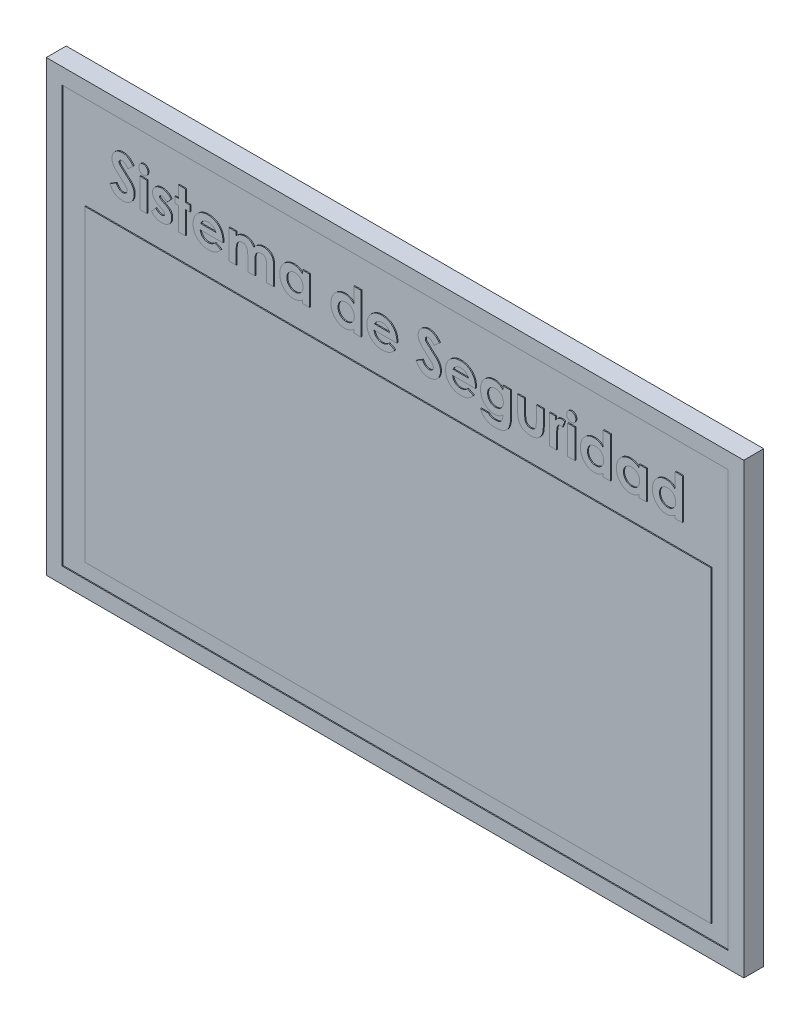
SolidWorks part; units mm, degrees
ref_plane "Alzado" through (0, 0, 0) normal (0, 0, 1) x (1, 0, 0)
ref_plane "Planta" through (0, 0, 0) normal (0, 1, 0) x (1, 0, 0)
ref_plane "Vista lateral" through (0, 0, 0) normal (1, 0, 0) x (0, 0, -1)
sketch "Croquis1" plane through (0, 0, 0) normal (0, 0, 1) x (1, 0, 0)
  line L1 (-350, -225) -> (350, -225)
  line L2 (-350, -225) -> (-350, 225)
  line L3 (-350, 225) -> (350, 225)
  line L4 (350, -225) -> (350, 225)
  line L5 (-350, -225) -> (350, 225) construction
  line L6 (-350, 225) -> (350, -225) construction
  point P0 (0, 0)
  dimension "D1" = 450
  dimension "D2" = 700
extrude "Saliente-Extruir1" add sketch "Croquis1" along normal blind 20
sketch "Croquis2" plane through (0, 0, 20) normal (0, 0, 1) x (1, 0, 0)
  line L0 (350, 225) -> (-350, 225) construction
  line L1 (334, -209) -> (-334, -209)
  line L2 (334, -209) -> (334, 209)
  line L3 (334, 209) -> (-334, 209)
  line L4 (-334, -209) -> (-334, 209)
  line L5 (334, -209) -> (-334, 209) construction
  line L6 (334, 209) -> (-334, -209) construction
  line L7 (350, -225) -> (350, 225) construction
  point P0 (0, 0)
  dimension "D1" = 16
  dimension "D2" = 16
extrude "Cortar-Extruir1" cut sketch "Croquis2" against normal blind 1
sketch "Croquis3" plane through (0, 0, 19) normal (0, 0, 1) x (1, 0, 0)
  line L0 (-287.6779, 139.8434) -> (288.4044, 139.8434) construction
  text T0 "Sistema de Seguridad" font "Century Gothic" height in points 150
extrude "Saliente-Extruir2" add sketch "Croquis3" along normal blind 1
sketch "Croquis4" plane through (0, 0, 19) normal (0, 0, 1) x (1, 0, 0)
  line L1 (-311.2125, 114.9747) -> (317.2703, 114.9747)
  line L2 (-311.2125, 114.9747) -> (-311.2125, -194.2057)
  line L3 (-311.2125, -194.2057) -> (317.2703, -194.2057)
  line L4 (317.2703, 114.9747) -> (317.2703, -194.2057)
extrude "Saliente-Extruir3" add sketch "Croquis4" along normal blind 1
